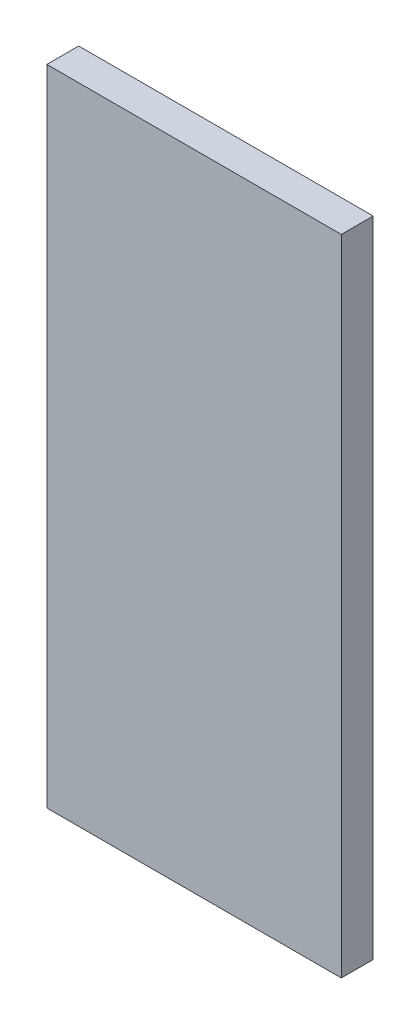
SolidWorks part; units mm, degrees
ref_plane "Front Plane" through (0, 0, 0) normal (0, 0, 1) x (1, 0, 0)
ref_plane "Top Plane" through (0, 0, 0) normal (0, 1, 0) x (1, 0, 0)
ref_plane "Right Plane" through (0, 0, 0) normal (1, 0, 0) x (0, 0, -1)
sketch "Sketch1" plane through (0, 0, 0) normal (0, 0, 1) x (1, 0, 0)
  line L0 (-18.1, -8.35) -> (-18.1, 13.87) construction
  line L1 (-18.1, 13.87) -> (-28.26, 13.87) construction
  line L2 (-28.26, 13.87) -> (-28.26, -8.35) construction
  line L3 (-28.26, -8.35) -> (-18.1, -8.35) construction
  line L4 (-18.1, -8.35) -> (-18.1, 13.87)
  line L5 (-18.1, 13.87) -> (-28.26, 13.87)
  line L6 (-28.26, 13.87) -> (-28.26, -8.35)
  line L7 (-28.26, -8.35) -> (-18.1, -8.35)
extrude "Extrude1" add sketch "Sketch1" along normal blind 1.1
